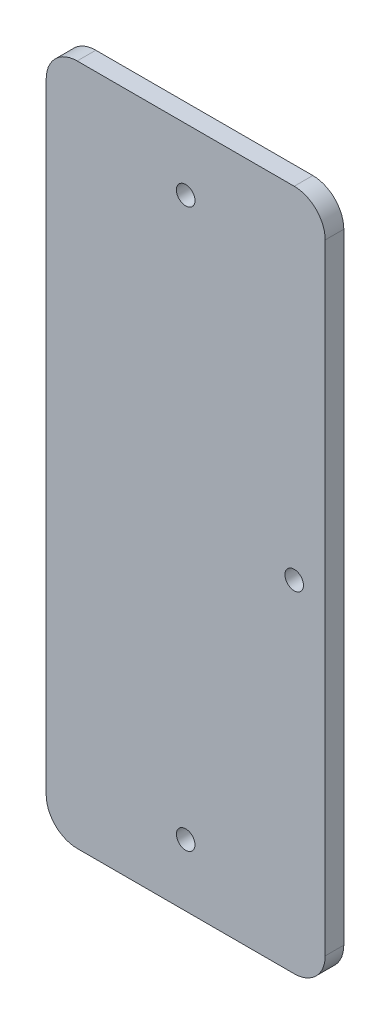
SolidWorks part; units mm, degrees
ref_plane "Front Plane" through (0, 0, 0) normal (0, 0, 1) x (1, 0, 0)
ref_plane "Top Plane" through (0, 0, 0) normal (0, 1, 0) x (1, 0, 0)
ref_plane "Right Plane" through (0, 0, 0) normal (1, 0, 0) x (0, 0, -1)
sketch "Sketch1" plane through (0, 0, 0) normal (0, 0, 1) x (1, 0, 0)
  line L1 (-17.5, 55) -> (17.5, 55)
  line L2 (-22.5, 50) -> (-22.5, -50)
  line L3 (-17.5, -55) -> (17.5, -55)
  line L4 (22.5, 50) -> (22.5, -50)
  line L5 (-22.5, 55) -> (22.5, -55) construction
  line L6 (-22.5, -55) -> (22.5, 55) construction
  arc A0 (-22.5, -50) -> (-17.5, -55) centre (-17.5, -50) ccw
  arc A1 (17.5, -55) -> (22.5, -50) centre (17.5, -50) ccw
  arc A2 (17.5, 55) -> (22.5, 50) centre (17.5, 50) cw
  arc A3 (-17.5, 55) -> (-22.5, 50) centre (-17.5, 50) ccw
  circle A4 centre (17.5, 0) radius 1.5
  point P0 (0, 0)
  point P20 (0, 0)
  dimension "D2" = 5
  dimension "D3" = 5
  dimension "D5" = 3
  dimension "D1" = 45
  dimension "D4" = 100
  dimension "D6" = 5
extrude "Boss-Extrude1" add sketch "Sketch1" along normal blind 3
hole_wizard "1/4-20 Tapped Hole1" [suppressed] positions "Sketch2" profile "Sketch3" tap size "1/4-20" standard "ANSI Inch"
sketch "Sketch2" plane through (0, 0, 3) normal (0, 0, 1) x (1, 0, 0)
  point P0 (0, 27)
  point P2 (0, -27)
  dimension "D1" = 27
  dimension "D2" = 27
sketch "Sketch3" plane through (0, 27, 3) normal (1, 0, 0) x (0, -1, 0)
  line L0 (0, 0) -> (0, 3)
  line L1 (0, 3) -> (2.5527, 3)
  line L2 (2.5527, 3) -> (2.5527, 0)
  line L5 (2.5527, 0) -> (0, 0)
  line L11 (0, -6.35) -> (0, 107.95) construction
  dimension "Thru Tap Drill Dia." = 5.1054
  dimension "Thru Tap Drill Depth" = 3
cosmetic thread "Hole Thread1" [suppressed] parameters "D2"=6.35
cosmetic thread "Hole Thread2" [suppressed] parameters "D2"=6.35
sketch "Sketch4" plane through (0, 0, 3) normal (0, 0, 1) x (1, 0, 0)
  circle A0 centre (0, 45) radius 1.5
  circle A1 centre (0, -45) radius 1.5
  dimension "D1" = 3
  dimension "D2" = 3
  dimension "D3" = 45
  dimension "D4" = 45
extrude "Cut-Extrude1" cut sketch "Sketch4" against normal through all
equation "\"D2@Sketch2\"=\"D1@Sketch2\""
equation "\"D4@Sketch4\"=\"D3@Sketch4\""
